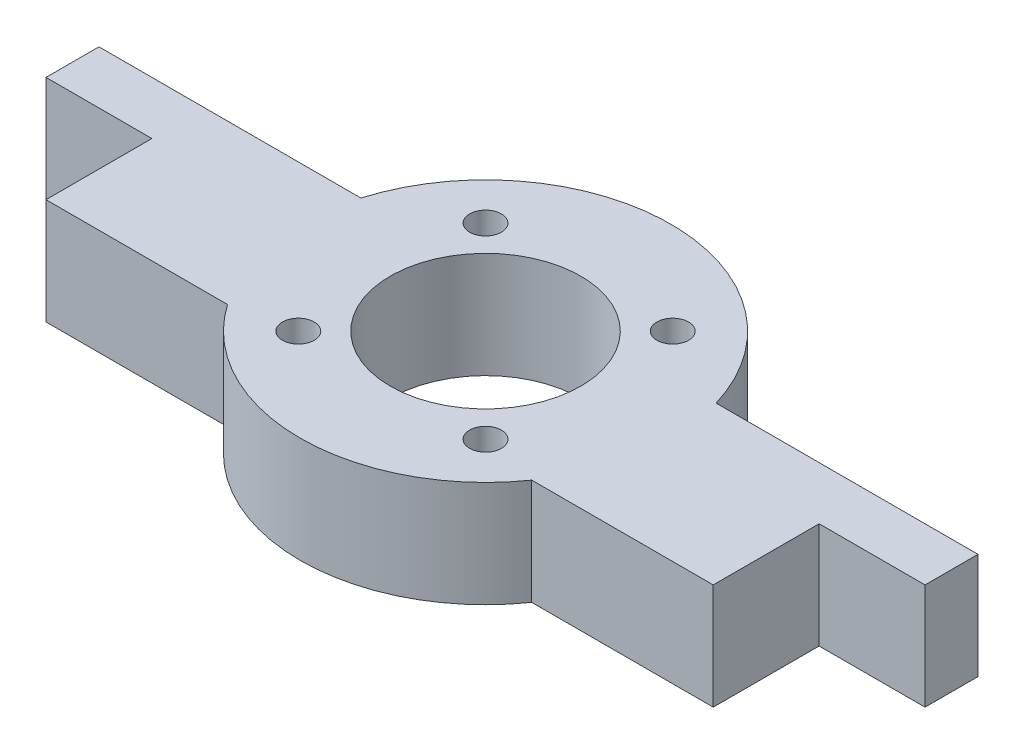
SolidWorks part; units mm, degrees
ref_plane "Спереди" through (0, 0, 0) normal (0, 0, 1) x (1, 0, 0)
ref_plane "Сверху" through (0, 0, 0) normal (0, 1, 0) x (1, 0, 0)
ref_plane "Справа" through (0, 0, 0) normal (1, 0, 0) x (0, 0, -1)
sketch "Эскиз1" plane through (0, 0, 0) normal (0, 1, 0) x (1, 0, 0)
  line L0 (0, 0) -> (34.3398, 0) construction
  line L1 (-8.8388, 8.8388) -> (8.8388, 8.8388) construction
  line L2 (-8.8388, 8.8388) -> (-8.8388, -8.8388) construction
  line L3 (-8.8388, -8.8388) -> (8.8388, -8.8388) construction
  line L4 (8.8388, 8.8388) -> (8.8388, -8.8388) construction
  line L5 (-8.8388, 8.8388) -> (8.8388, -8.8388) construction
  line L6 (-8.8388, -8.8388) -> (8.8388, 8.8388) construction
  line L7 (0, 0) -> (0, -38.1414) construction
  line L9 (-31.5, 0) -> (-31.5, -10)
  line L10 (-31.5, -10) -> (-14.3614, -10)
  line L11 (31.5, 0) -> (31.5, -10)
  line L12 (-41.5, 5) -> (-16.7705, 5)
  line L13 (-41.5, 5) -> (-41.5, 0)
  line L14 (14.3614, -10) -> (31.5, -10)
  line L15 (41.5, 5) -> (41.5, 0)
  line L16 (16.7705, 5) -> (41.5, 5)
  line L17 (41.5, 0) -> (31.5, 0)
  line L18 (-41.5, 0) -> (-31.5, 0)
  circle A0 centre (0, 0) radius 9
  circle A1 centre (-8.8388, 8.8388) radius 1.5
  circle A2 centre (8.8388, 8.8388) radius 1.5
  circle A3 centre (8.8388, -8.8388) radius 1.5
  circle A4 centre (-8.8388, -8.8388) radius 1.5
  arc A5 (-14.3614, -10) -> (14.3614, -10) centre (0, 0) ccw
  arc A6 (16.7705, 5) -> (-16.7705, 5) centre (0, 0) ccw
  dimension "D1" = 18
  dimension "D3" = 3
  dimension "D6" = 35
  dimension "D2" = 25
  dimension "D4" = 63
  dimension "D5" = 10
  dimension "D7" = 5
  dimension "D8" = 10
sketch "Эскиз2" plane through (0, 0, 0) normal (0, 1, 0) x (1, 0, 0)
extrude "Бобышка-Вытянуть1" add sketch "Эскиз1" along normal blind 10
